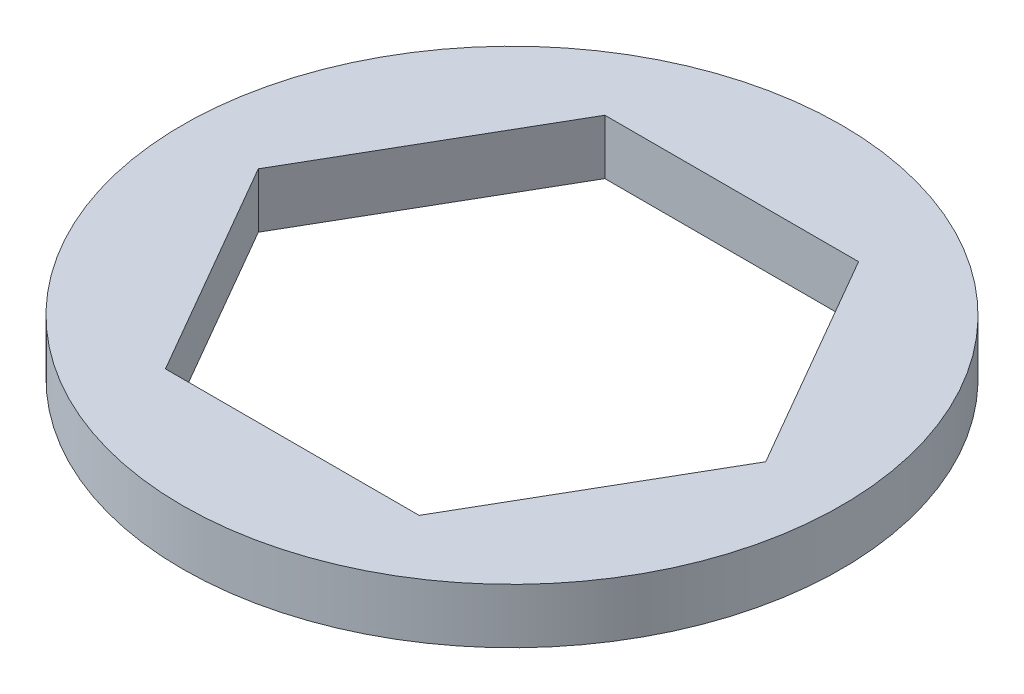
SolidWorks part; units mm, degrees
material "PET"
ref_plane "Front Plane" through (0, 0, 0) normal (0, 0, 1) x (1, 0, 0)
ref_plane "Top Plane" through (0, 0, 0) normal (0, 1, 0) x (1, 0, 0)
ref_plane "Right Plane" through (0, 0, 0) normal (1, 0, 0) x (0, 0, -1)
sketch "Sketch1" plane through (0, 0, 0) normal (0, 1, 0) x (1, 0, 0)
  line L1 (7.3323, 0) -> (3.6662, 6.35)
  line L2 (3.6662, 6.35) -> (-3.6662, 6.35)
  line L3 (-3.6662, 6.35) -> (-7.3323, 0)
  line L4 (-7.3323, 0) -> (-3.6662, -6.35)
  line L5 (-3.6662, -6.35) -> (3.6662, -6.35)
  line L6 (3.6662, -6.35) -> (7.3323, 0)
  circle A0 centre (0, 0) radius 6.35 construction
  circle A1 centre (0, 0) radius 9.525
  dimension "D1" = 19.05
  dimension "D2" = 12.7
extrude "Boss-Extrude1" add sketch "Sketch1" along normal blind 1.5875
